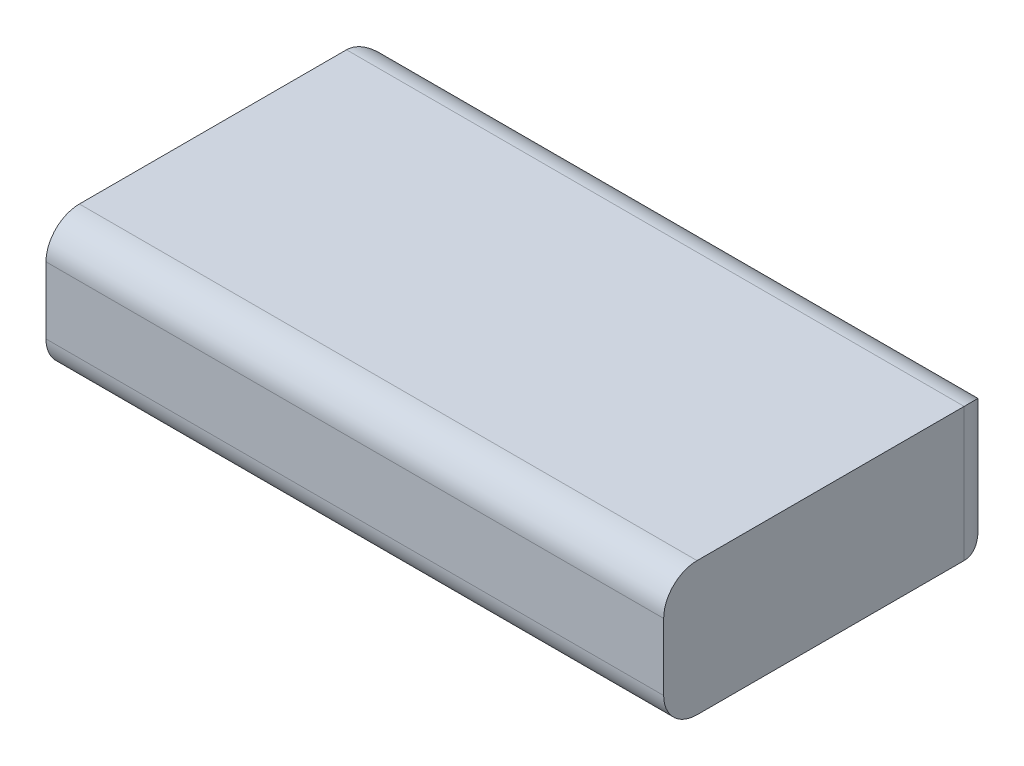
SolidWorks part; units mm, degrees
ref_plane "Front Plane" through (0, 0, 0) normal (0, 0, 1) x (1, 0, 0)
ref_plane "Top Plane" through (0, 0, 0) normal (0, 1, 0) x (1, 0, 0)
ref_plane "Right Plane" through (0, 0, 0) normal (1, 0, 0) x (0, 0, -1)
sketch "Sketch1" plane through (0, 0, 0) normal (0, 1, 0) x (1, 0, 0)
  line L1 (0, 0) -> (37, 0)
  line L2 (0, 0) -> (0, 20)
  line L3 (0, 20) -> (37, 20)
  line L4 (37, 0) -> (37, 20)
  dimension "D1" = 37
  dimension "D2" = 20
extrude "Boss-Extrude1" add sketch "Sketch1" along normal blind 8
fillet "Fillet1" radius 2 1 edges at (18.5, 8, 0)
fillet "Fillet2" radius 2 5 edges at (37, 4, -20) (18.5, 8, -20) (0, 4, -20) (18.5, 0, -20) (18.5, 0, 0)
